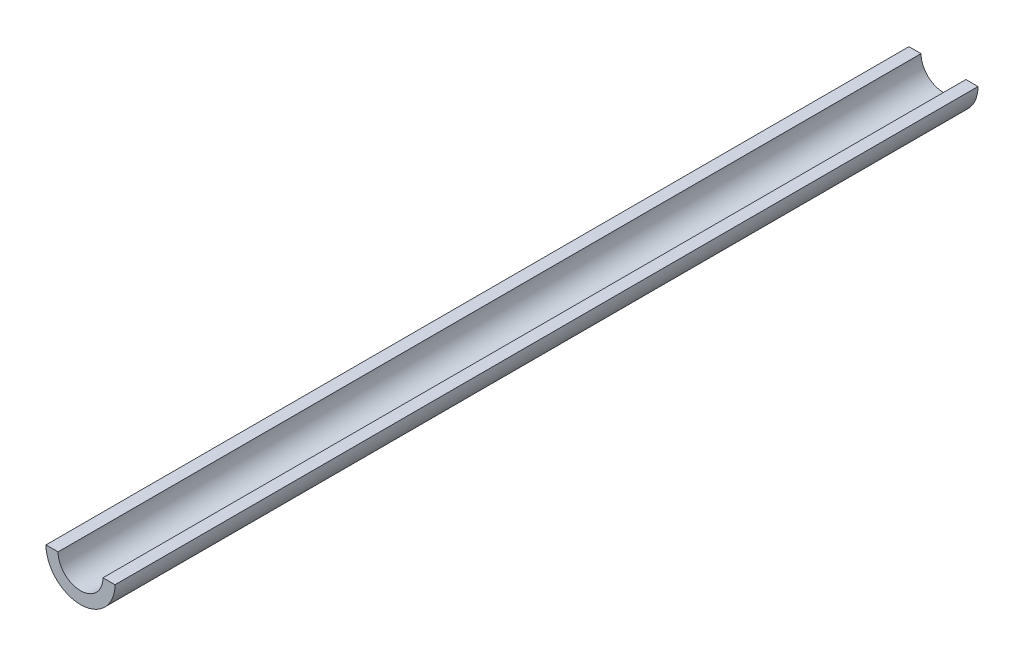
SolidWorks part; units mm, degrees
ref_plane "前视基准面" through (0, 0, 0) normal (0, 0, 1) x (1, 0, 0)
ref_plane "上视基准面" through (0, 0, 0) normal (0, 1, 0) x (1, 0, 0)
ref_plane "右视基准面" through (0, 0, 0) normal (1, 0, 0) x (0, 0, -1)
sketch "草图3" plane through (0, 0, 0) normal (0, 0, 1) x (1, 0, 0)
  line L0 (-10, 0) -> (-6.5, 0)
  line L1 (6.5, 0) -> (10, 0)
  arc A0 (-10, 0) -> (10, 0) centre (0, 0) ccw
  arc A1 (-6.5, 0) -> (6.5, 0) centre (0, 0) ccw
  dimension "D1" = 20
  dimension "D2" = 13
extrude "凸台-拉伸1" add sketch "草图3" along normal blind 250
